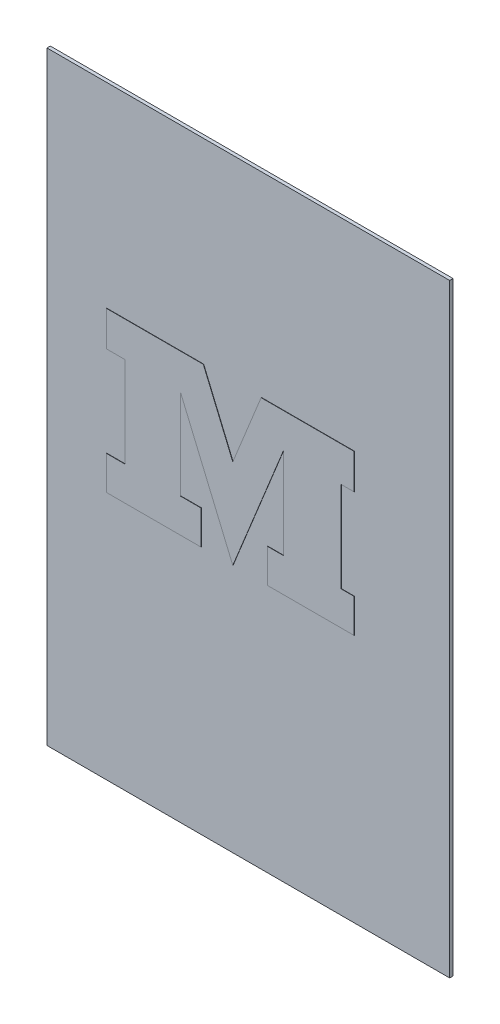
SolidWorks part; units mm, degrees
ref_plane "Front Plane" through (0, 0, 0) normal (0, 0, 1) x (1, 0, 0)
ref_plane "Top Plane" through (0, 0, 0) normal (0, 1, 0) x (1, 0, 0)
ref_plane "Right Plane" through (0, 0, 0) normal (1, 0, 0) x (0, 0, -1)
sketch "Sketch1" plane through (0, 0, 0) normal (0, 0, 1) x (1, 0, 0)
  line L1 (0, 0) -> (304.8, 0)
  line L2 (0, 0) -> (0, 457.2)
  line L3 (0, 457.2) -> (304.8, 457.2)
  line L4 (304.8, 0) -> (304.8, 457.2)
  dimension "D1" = 457.2
  dimension "D2" = 304.8
extrude "Boss-Extrude1" add sketch "Sketch1" along normal blind 2.54
sketch "Sketch2" plane through (0, 0, 2.54) normal (0, 0, 1) x (1, 0, 0)
  line L0 (76.5826, 188.5998) -> (116.8443, 188.5998)
  line L1 (116.8443, 188.5998) -> (116.8443, 214.2208)
  line L2 (116.8443, 214.2208) -> (101.1579, 214.2208)
  line L3 (101.1579, 214.2208) -> (101.1579, 282.7179)
  line L4 (101.1579, 282.7179) -> (140.8967, 188.5998)
  line L5 (140.8967, 188.5998) -> (179.1322, 282.7179)
  line L6 (179.1322, 282.7179) -> (179.1322, 214.2208)
  line L7 (179.1322, 214.2208) -> (167.0671, 214.2208)
  line L8 (167.0671, 214.2208) -> (167.0671, 188.5998)
  line L9 (167.0671, 188.5998) -> (232.7531, 188.5998)
  line L10 (232.7531, 188.5998) -> (232.7531, 214.2208)
  line L11 (232.7531, 214.2208) -> (222.9002, 214.2208)
  line L12 (222.9002, 214.2208) -> (222.9002, 282.7179)
  line L13 (222.9002, 309.2717) -> (162.3435, 309.2717)
  line L14 (162.3435, 309.2717) -> (140.8967, 256.4795)
  line L15 (140.8967, 256.4795) -> (118.6066, 309.2717)
  line L16 (118.6066, 309.2717) -> (59.1968, 309.2717)
  line L17 (59.1968, 282.7179) -> (59.1968, 214.2208)
  line L18 (59.1968, 214.2208) -> (45.2349, 214.2208)
  line L19 (45.2349, 214.2208) -> (45.2349, 188.5998)
  line L20 (45.2349, 188.5998) -> (76.5826, 188.5998)
  line L21 (59.1968, 282.7179) -> (45.2349, 282.7179)
  line L22 (45.2349, 282.7179) -> (45.2349, 309.2717)
  line L23 (45.2349, 309.2717) -> (59.1968, 309.2717)
  line L24 (222.9002, 282.7179) -> (232.7531, 282.7179)
  line L25 (232.7531, 282.7179) -> (232.7531, 309.2717)
  line L26 (232.7531, 309.2717) -> (222.9002, 309.2717)
extrude "Boss-Extrude2" add sketch "Sketch2" along normal blind 0.254
